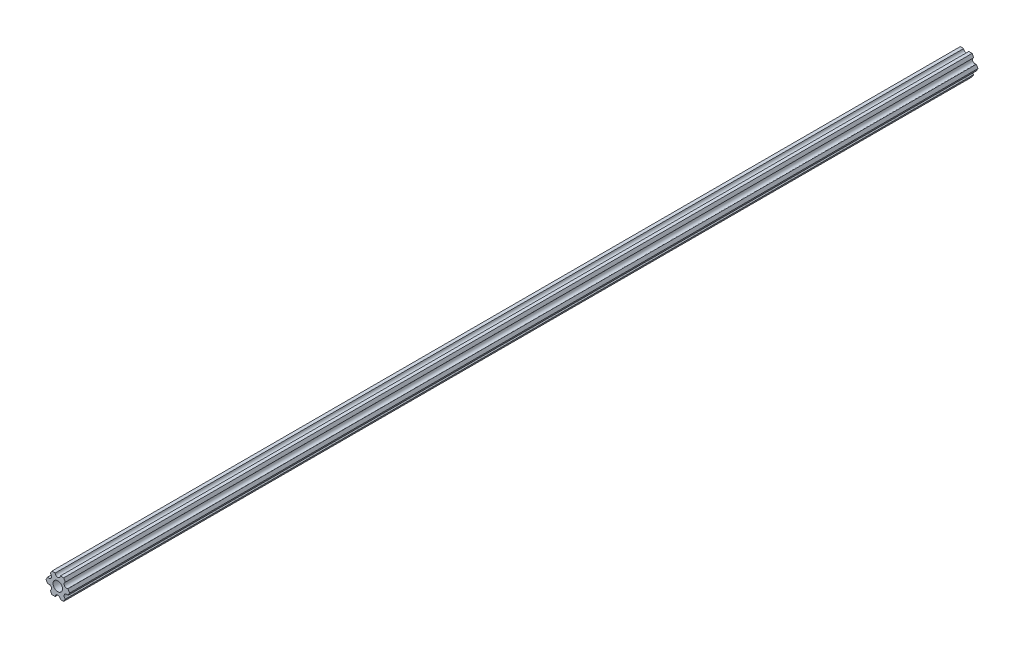
SolidWorks part; units mm, degrees
ref_plane "Front Plane" through (0, 0, 0) normal (0, 0, 1) x (1, 0, 0)
ref_plane "Top Plane" through (0, 0, 0) normal (0, 1, 0) x (1, 0, 0)
ref_plane "Right Plane" through (0, 0, 0) normal (1, 0, 0) x (0, 0, -1)
sketch "Sketch1" plane through (0, 0, 0) normal (0, 0, 1) x (1, 0, 0)
  line L0 (-1.5875, 6.35) -> (-3.6662, 6.35)
  line L1 (7.3323, 0) -> (6.293, 1.8002)
  line L2 (3.6662, 6.35) -> (1.5875, 6.35)
  line L3 (-3.6662, 6.35) -> (-4.7055, 4.5498)
  line L4 (-7.3323, 0) -> (-6.293, -1.8002)
  line L5 (-3.6662, -6.35) -> (-1.5875, -6.35)
  line L6 (3.6662, -6.35) -> (4.7055, -4.5498)
  line L7 (-6.293, 1.8002) -> (-7.3323, 0)
  line L8 (-4.7055, -4.5498) -> (-3.6662, -6.35)
  line L9 (1.5875, -6.35) -> (3.6662, -6.35)
  line L10 (6.293, -1.8002) -> (7.3323, 0)
  line L11 (4.7055, 4.5498) -> (3.6662, 6.35)
  circle A0 centre (0, 0) radius 2.9337
  arc A2 (-1.5875, 6.35) -> (1.5875, 6.35) centre (0, 6.35) ccw
  arc A3 (4.7055, 4.5498) -> (6.293, 1.8002) centre (5.4993, 3.175) ccw
  arc A4 (6.293, -1.8002) -> (4.7055, -4.5498) centre (5.4993, -3.175) ccw
  arc A5 (1.5875, -6.35) -> (-1.5875, -6.35) centre (0, -6.35) ccw
  arc A6 (-4.7055, -4.5498) -> (-6.293, -1.8002) centre (-5.4993, -3.175) ccw
  arc A7 (-6.293, 1.8002) -> (-4.7055, 4.5498) centre (-5.4993, 3.175) ccw
  dimension "D1" = 5.8674
  dimension "D3" = 3.175
  dimension "D4" = 6
extrude "Boss-Extrude1" add sketch "Sketch1" along normal mid plane 565.15
